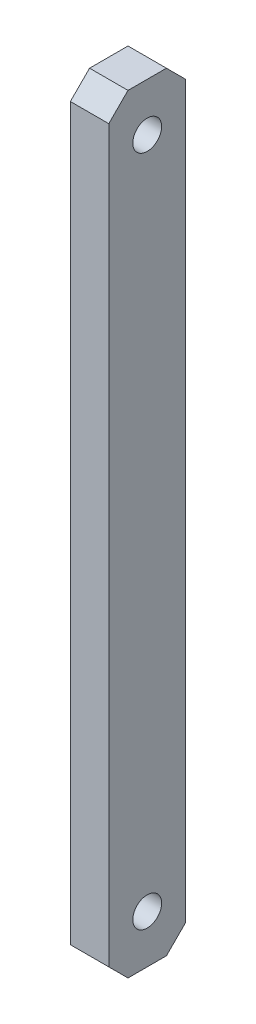
SolidWorks part; units mm, degrees
ref_plane "Front Plane" through (0, 0, 0) normal (0, 0, 1) x (1, 0, 0)
ref_plane "Top Plane" through (0, 0, 0) normal (0, 1, 0) x (1, 0, 0)
ref_plane "Right Plane" through (0, 0, 0) normal (1, 0, 0) x (0, 0, -1)
sketch "Sketch1" plane through (0, 0, 0) normal (1, 0, 0) x (0, 0, -1)
  line L0 (0, 35) -> (0, -35) construction
  line L1 (-4, -40) -> (4, -40)
  line L2 (-4, -40) -> (-4, 40)
  line L3 (-4, 40) -> (4, 40)
  line L4 (4, -40) -> (4, 40)
  line L5 (-4, -40) -> (4, 40) construction
  line L6 (-4, 40) -> (4, -40) construction
  circle A0 centre (0, -35) radius 1.5
  circle A1 centre (0, 35) radius 1.5
  point P0 (0, 0)
  point P10 (0, 0)
  dimension "D3" = 3
  dimension "D1" = 8
  dimension "D2" = 80
  dimension "D4" = 70
  dimension "D5" = 4
extrude "Boss-Extrude1" add sketch "Sketch1" along normal blind 4
chamfer "Chamfer1" distance 2 angle 45 4 edges at (2, -40, -4) (2, -40, 4) (2, 40, 4) (2, 40, -4)
